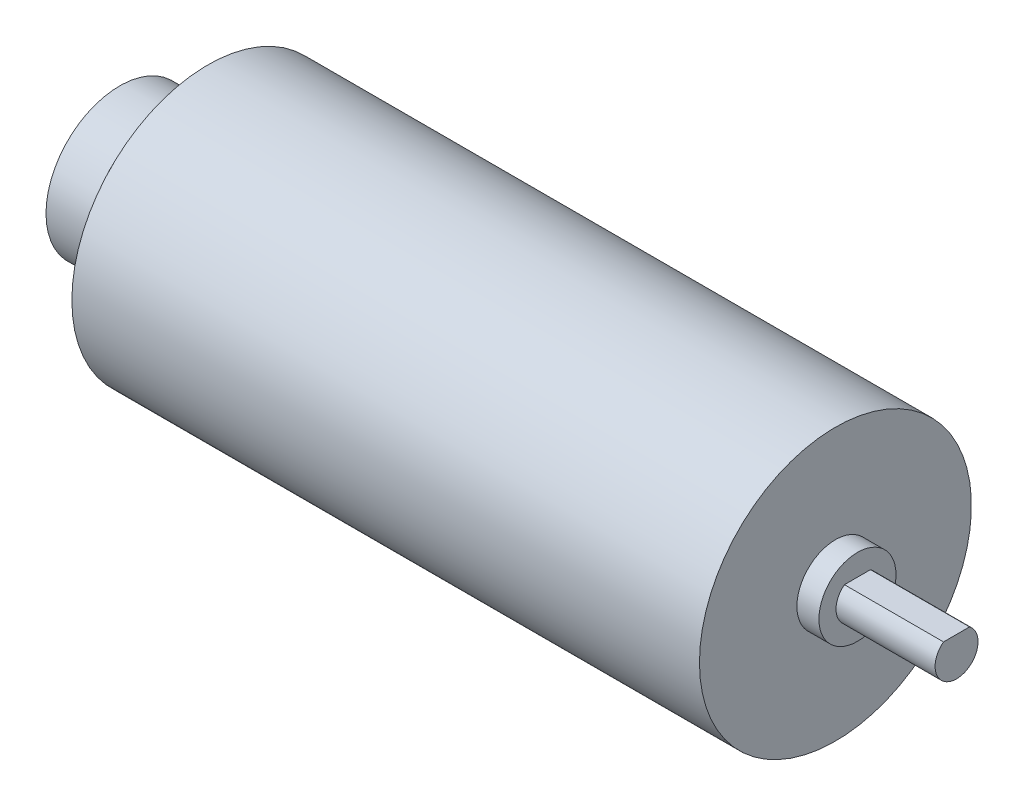
SolidWorks part; units mm, degrees
ref_plane "Front" through (0, 0, 0) normal (0, 0, 1) x (1, 0, 0)
ref_plane "Top" through (0, 0, 0) normal (0, 1, 0) x (1, 0, 0)
ref_plane "Right" through (0, 0, 0) normal (1, 0, 0) x (0, 0, -1)
sketch "Эскиз1" plane through (0, 0, 0) normal (0, 1, 0) x (1, 0, 0)
  line L0 (-28.5, 0) -> (28.5, 0) construction
  line L1 (-28.5, 0) -> (28.5, 0)
  line L2 (-28.5, 12.35) -> (28.5, 12.35)
  line L3 (-28.5, 12.35) -> (-28.5, 0)
  line L5 (28.5, 12.35) -> (28.5, 0)
  point P3 (0, 0)
  dimension "D1" = 57
  dimension "D2" = 12.35
revolve "Повернуть1" add sketch "Эскиз1" angle 360 about L1
sketch "Эскиз2" plane through (28.5, 0, 0) normal (1, 0, 0) x (0, 0, -1)
  circle A0 centre (0, 0) radius 3.5
  dimension "D1" = 7
extrude "Бобышка-Вытянуть1" add sketch "Эскиз2" along normal blind 2
sketch "Эскиз3" plane through (30.5, 0, 0) normal (1, 0, 0) x (0, 0, -1)
  line L0 (-1.1832, 1.55) -> (1.1832, 1.55)
  circle A0 centre (0, 0) radius 1.95
  dimension "D1" = 3.9
  dimension "D2" = 1.55
sketch "Эскиз5" plane through (-28.5, 0, 0) normal (-1, 0, 0) x (0, 0, 1)
  circle A0 centre (0, 0) radius 0.75
  dimension "D1" = 1.5
extrude "Бобышка-Вытянуть3" add sketch "Эскиз5" along normal blind 4
sketch "Эскиз6" plane through (-32.5, 0, 0) normal (-1, 0, 0) x (0, 0, 1)
  circle A0 centre (0, 0) radius 6.7
  dimension "D1" = 13.4
extrude "Бобышка-Вытянуть4" add sketch "Эскиз6" along normal blind 4
extrude "Бобышка-Вытянуть5" add sketch "Эскиз3" along normal blind 9 contours L0 A0
